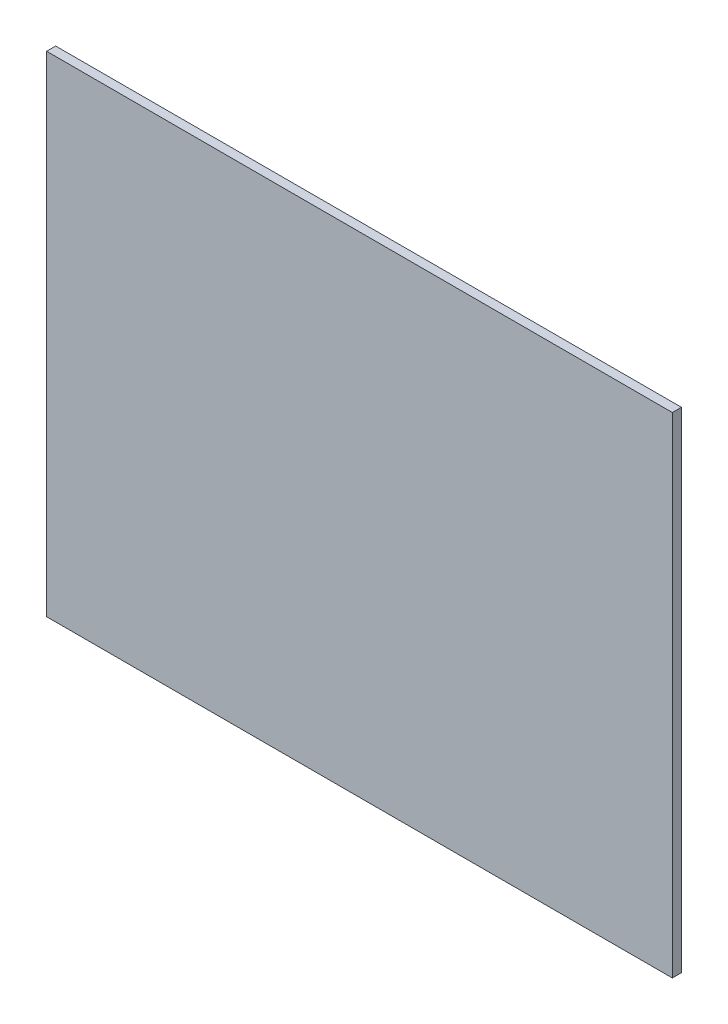
SolidWorks part; units mm, degrees
ref_plane "Front Plane" through (0, 0, 0) normal (1, 0, 0) x (0, 1, 0)
ref_plane "Top Plane" through (0, 0, 0) normal (0, 0, 1) x (0, 1, 0)
ref_plane "Right Plane" through (0, 0, 0) normal (0, 1, 0) x (-1, 0, 0)
sketch "Sketch1" plane through (0, 0, 0) normal (0, 0, 1) x (0, 1, 0)
  line L1 (0, 0) -> (270, 0)
  line L2 (0, 0) -> (0, 345)
  line L3 (0, 345) -> (270, 345)
  line L4 (270, 0) -> (270, 345)
  dimension "D1" = 345
  dimension "D2" = 270
extrude "Boss-Extrude1" add sketch "Sketch1" along normal blind 5 contours L3 L4 L1 L2
